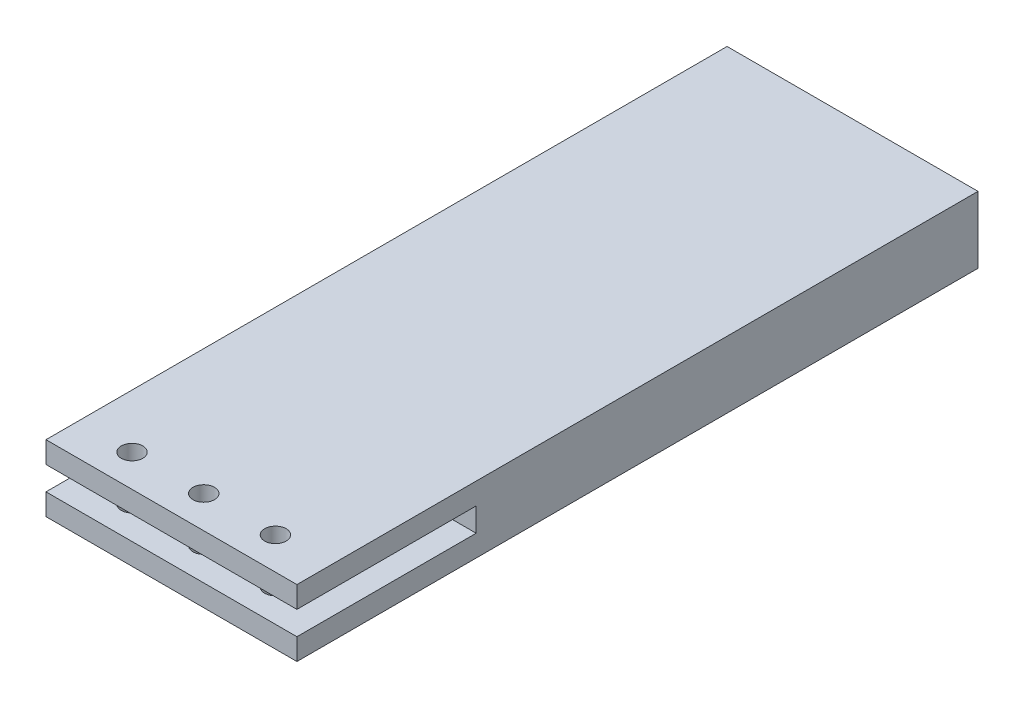
SolidWorks part; units mm, degrees
ref_plane "前视基准面" through (0, 0, 0) normal (0, 0, 1) x (1, 0, 0)
ref_plane "上视基准面" through (0, 0, 0) normal (0, 1, 0) x (1, 0, 0)
ref_plane "右视基准面" through (0, 0, 0) normal (1, 0, 0) x (0, 0, -1)
other "Configuration Table"
sketch "草图1" plane through (0, 0, 0) normal (0, 0, 1) x (1, 0, 0)
  line L1 (0, 0) -> (35, 0) construction
  line L2 (0, 0) -> (0, -3.3) construction
  line L3 (0, -3.3) -> (35, -3.3) construction
  line L4 (35, 0) -> (35, -3.3) construction
  line L5 (0, 0) -> (35, 0)
  line L6 (0, 0) -> (0, 3)
  line L7 (0, 3) -> (35, 3)
  line L8 (35, 0) -> (35, 3)
  line L9 (0, -3.3) -> (35, -3.3)
  line L10 (0, -3.3) -> (0, -6.3)
  line L11 (0, -6.3) -> (35, -6.3)
  line L12 (35, -3.3) -> (35, -6.3)
  dimension "D1" = 3.3
  dimension "D2" = 35
  dimension "D3" = 3
  dimension "D4" = 3
extrude "凸台-拉伸1" add sketch "草图1" along normal blind 25
sketch "草图2" plane through (0, 0, 0) normal (0, 0, -1) x (-1, 0, 0)
  line L1 (-35, 3) -> (0, 3)
  line L2 (-35, 3) -> (-35, -6.3)
  line L3 (-35, -6.3) -> (0, -6.3)
  line L4 (0, 3) -> (0, -6.3)
extrude "凸台-拉伸2" add sketch "草图2" along normal blind 70
sketch "草图3" plane through (0, 3, 0) normal (0, 1, 0) x (1, 0, 0)
  line L0 (35, -25) -> (0, -25) construction
  line L1 (0, -25) -> (0, 70) construction
  line L2 (35, -25) -> (35, 70) construction
  circle A0 centre (7.5, -20.5) radius 1.5
  circle A1 centre (17.5, -20.5) radius 1.5
  circle A2 centre (27.5, -20.5) radius 1.5
  dimension "D1" = 3
  dimension "D2" = 3
  dimension "D3" = 3
  dimension "D4" = 4.5
  dimension "D5" = 7.5
  dimension "D6" = 7.5
  dimension "D7" = 10
extrude "切除-拉伸1" cut sketch "草图3" against normal blind 10
